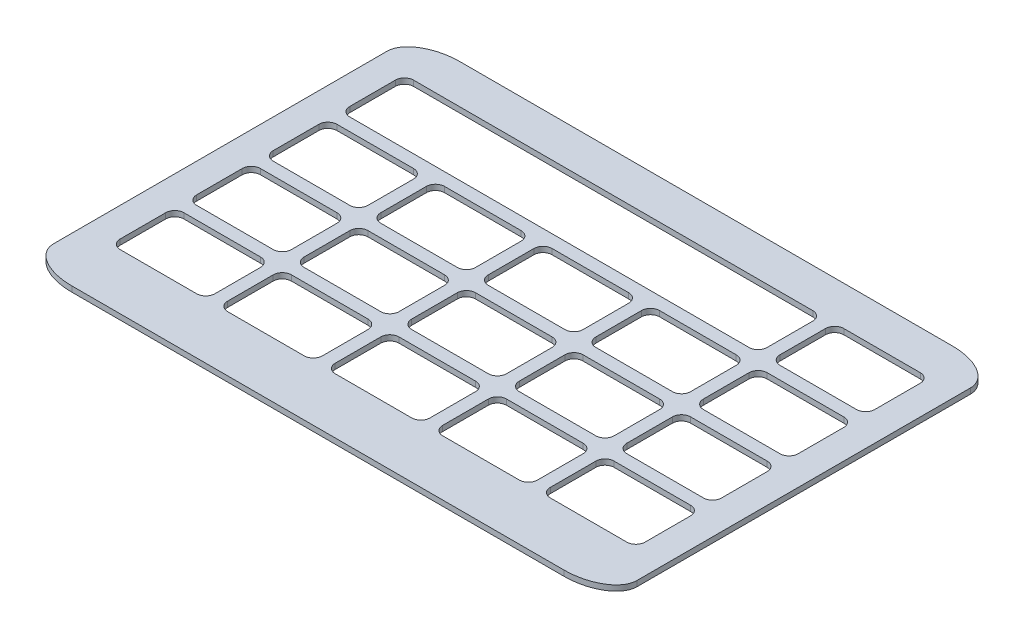
SolidWorks part; units mm, degrees
ref_plane "Front Plane" through (0, 0, 0) normal (0, 0, 1) x (1, 0, 0)
ref_plane "Top Plane" through (0, 0, 0) normal (0, 1, 0) x (1, 0, 0)
ref_plane "Right Plane" through (0, 0, 0) normal (1, 0, 0) x (0, 0, -1)
sketch "Sketch1" plane through (0, 0, 0) normal (0, 1, 0) x (1, 0, 0)
  line L1 (-160, -106.5) -> (160, -106.5)
  line L2 (-160, -106.5) -> (-160, 106.5)
  line L3 (-160, 106.5) -> (160, 106.5)
  line L4 (160, -106.5) -> (160, 106.5)
  line L5 (-160, -106.5) -> (160, 106.5) construction
  line L6 (-160, 106.5) -> (160, -106.5) construction
  point P0 (0, 0)
  dimension "D1" = 320
  dimension "D2" = 213
extrude "Outer Profile" add sketch "Sketch1" along normal blind 3
sketch "Sketch3" plane through (0, 3, 0) normal (0, 1, 0) x (1, 0, 0)
  line L0 (-160, -106.5) -> (160, -106.5) construction
  line L1 (-147, -78.5) -> (147, -78.5) construction
  line L2 (-147, -78.5) -> (-147, 87.5) construction
  line L3 (-147, 87.5) -> (147, 87.5) construction
  line L4 (147, -78.5) -> (147, 87.5) construction
  line L5 (-147, -78.5) -> (147, 87.5) construction
  line L6 (-147, 87.5) -> (147, -78.5) construction
  point P0 (0, 4.5)
  dimension "D1" = 294
  dimension "D2" = 166
  dimension "D3" = 28
sketch "Sketch5" plane through (0, 3, 0) normal (0, 1, 0) x (1, 0, 0)
  line L0 (-147, -78.5) -> (147, -78.5) construction
  line L1 (-144, -76) -> (-92, -76)
  line L2 (-144, -76) -> (-144, -41)
  line L3 (-144, -41) -> (-92, -41)
  line L4 (-92, -76) -> (-92, -41)
  line L5 (-147, -78.5) -> (-147, 87.5) construction
  dimension "D1" = 52
  dimension "D2" = 35
  dimension "D3" = 2.5
  dimension "D4" = 3
extrude "Cutout" cut sketch "Sketch5" against normal through all
fillet "Corner Rad" radius 5 4 edges at (-92, 1.5, 76) (-92, 1.5, 41) (-144, 1.5, 41) (-144, 1.5, 76)
pattern_linear "LPattern1" count 5 spacing 59 along (1, 0, 0) count 4 spacing 42 along (0, 0, -1) of "Cutout", "Corner Rad"
sketch "Sketch6" plane through (0, 3, 0) normal (0, 1, 0) x (1, 0, 0)
  line L2 (160, 106.5) -> (-160, 106.5) construction
  line L3 (-160, 106.5) -> (-160, -106.5) construction
  line L4 (-135, 106.5) -> (-160, 106.5)
  line L5 (-160, 106.5) -> (-160, 91.5)
  ellipse E0 centre (-135, 91.5) end of major axis (-110, 91.5) minor radius 15 (-160, 91.5) -> (-135, 106.5) cw
  dimension "D1" = 15
  dimension "D2" = 25
extrude "Corner" cut sketch "Sketch6" against normal through all
mirror "CornersA" about plane through (0, 0, 0) normal (1, 0, 0) of "Corner"
mirror "CornersB" about plane through (0, 0, 0) normal (0, 0, 1) of "Corner", "CornersA"
sketch "Sketch7" plane through (0, 3, 0) normal (0, 1, 0) x (1, 0, 0)
  line L1 (-97, 50) -> (38, 50)
  line L2 (-97, 50) -> (-97, 85)
  line L3 (-97, 85) -> (38, 85)
  line L4 (38, 50) -> (38, 85)
extrude "Cut-Extrude2" cut sketch "Sketch7" against normal through all
chamfer "Chamfer1" [suppressed] distance 1 angle 45
